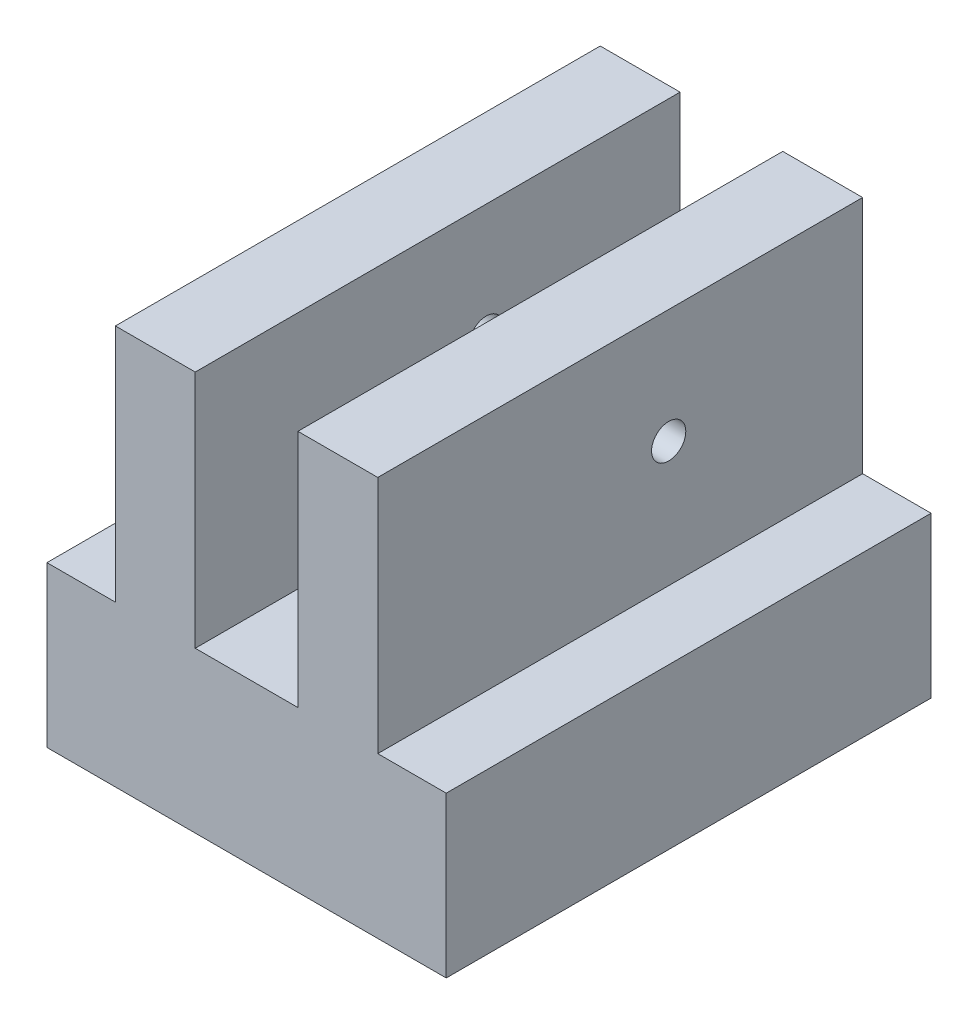
SolidWorks part; units mm, degrees
ref_plane "Front Plane" through (0, 0, 0) normal (0, 0, 1) x (1, 0, 0)
ref_plane "Top Plane" through (0, 0, 0) normal (0, 1, 0) x (1, 0, 0)
ref_plane "Right Plane" through (0, 0, 0) normal (1, 0, 0) x (0, 0, -1)
sketch "Sketch1" plane through (0, 0, 0) normal (0, 1, 0) x (1, 0, 0)
  line L1 (-35, 42.5) -> (35, 42.5)
  line L2 (-35, 42.5) -> (-35, -42.5)
  line L3 (-35, -42.5) -> (35, -42.5)
  line L4 (35, 42.5) -> (35, -42.5)
  line L5 (-35, 42.5) -> (35, -42.5) construction
  line L6 (-35, -42.5) -> (35, 42.5) construction
  point P0 (0, 0)
extrude "Boss-Extrude1" add sketch "Sketch1" along normal blind 70
sketch "Sketch2" plane through (0, 0, 0) normal (0, -1, 0) x (1, 0, 0)
  circle A0 centre (0, 0) radius 5
extrude "Cut-Extrude1" cut sketch "Sketch2" against normal blind 20
sketch "Sketch3" plane through (0, 0, -42.5) normal (0, 0, -1) x (-1, 0, 0)
  line L0 (0, 70) -> (0, 47.5242) construction
  line L2 (-35, 70) -> (-35, 0) construction
  line L3 (-47.7491, 73.3711) -> (-23, 73.3711)
  line L4 (-47.7491, 73.3711) -> (-47.7491, 28.0643)
  line L5 (-47.7491, 28.0643) -> (-23, 28.0643)
  line L6 (-23, 73.3711) -> (-23, 28.0643)
  line L7 (23, 73.3711) -> (23, 28.0643)
  line L8 (47.7491, 28.0643) -> (23, 28.0643)
  line L9 (47.7491, 73.3711) -> (47.7491, 28.0643)
  line L10 (47.7491, 73.3711) -> (23, 73.3711)
  dimension "D1" = 12
extrude "Cut-Extrude2" cut sketch "Sketch3" against normal through all
sketch "Sketch4" plane through (-23, 0, 0) normal (-1, 0, 0) x (0, 0, 1)
  line L0 (-42.5, 70) -> (-42.5, 28.0643) construction
  line L1 (-42.5, 0) -> (42.5, 0) construction
  circle A0 centre (-8.5, 50) radius 3
  dimension "D1" = 34
  dimension "D2" = 50
extrude "Cut-Extrude3" cut sketch "Sketch4" against normal through all
sketch "Sketch6" plane through (0, 0, -42.5) normal (0, 0, -1) x (-1, 0, 0)
  line L0 (0, 70) -> (0, 42.3349) construction
  line L2 (-23, 28.0643) -> (23, 28.0643) construction
  line L3 (-9, 90.8433) -> (9, 90.8433)
  line L4 (-9, 90.8433) -> (-9, 28.0643)
  line L5 (-9, 28.0643) -> (9, 28.0643)
  line L6 (9, 90.8433) -> (9, 28.0643)
  line L7 (-9, 90.8433) -> (9, 28.0643) construction
  line L8 (-9, 28.0643) -> (9, 90.8433) construction
  point P1 (0, 59.4538)
extrude "Cut-Extrude4" cut sketch "Sketch6" against normal through all
